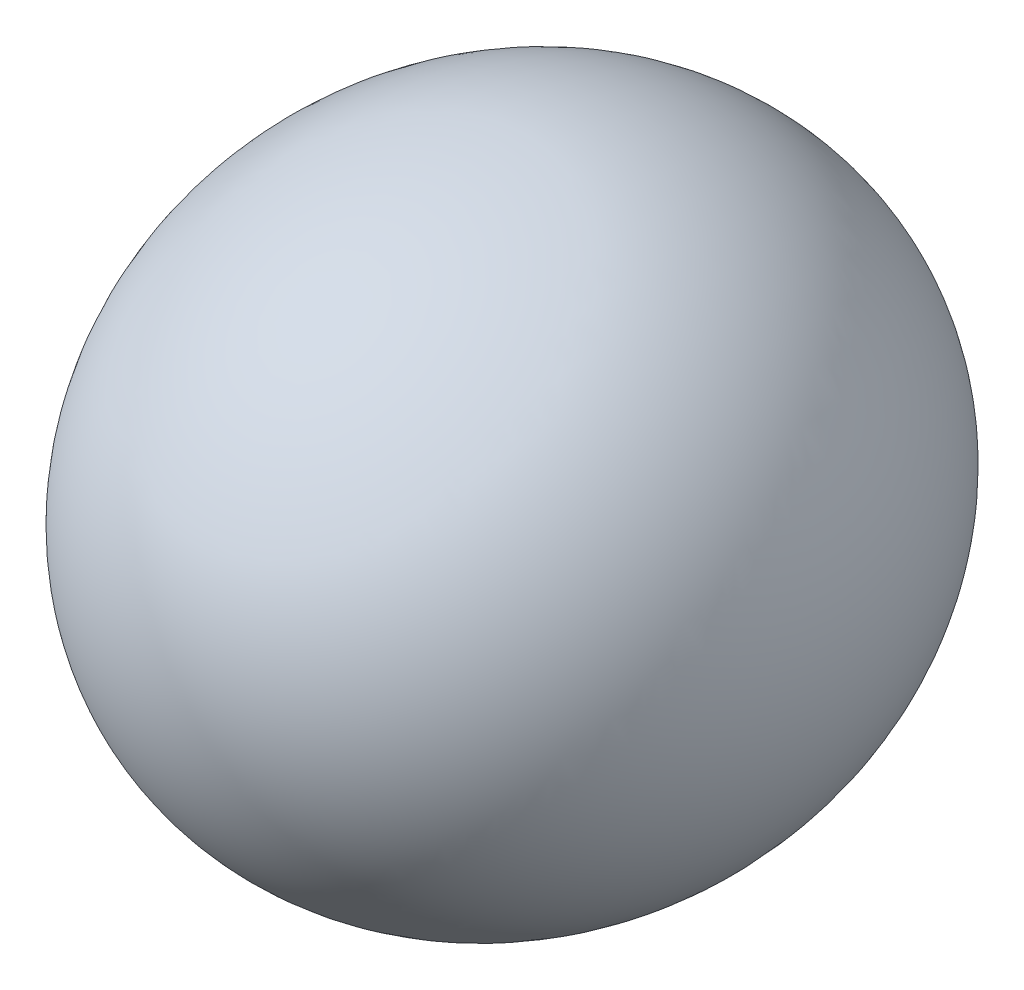
SolidWorks part; units mm, degrees
ref_plane "Front Plane" through (0, 0, 0) normal (0, 0, 1) x (1, 0, 0)
ref_plane "Top Plane" through (0, 0, 0) normal (0, 1, 0) x (1, 0, 0)
ref_plane "Right Plane" through (0, 0, 0) normal (1, 0, 0) x (0, 0, -1)
sketch "Sketch1" plane through (0, 0, 0) normal (0, 1, 0) x (1, 0, 0)
  line L0 (0, -1229.135) -> (0, 60227.6143) construction
  line L1 (0, 68.6848) -> (0, -68.6848)
  ellipse E0 centre (0, 0) end of major axis (0, -68.6848) minor radius 61.4357 (0, -68.6848) -> (0, 68.6848) ccw
  point P3 (0, 0)
  point P7 (0, 0)
revolve "Revolve1" add sketch "Sketch1" angle 360 about L0
